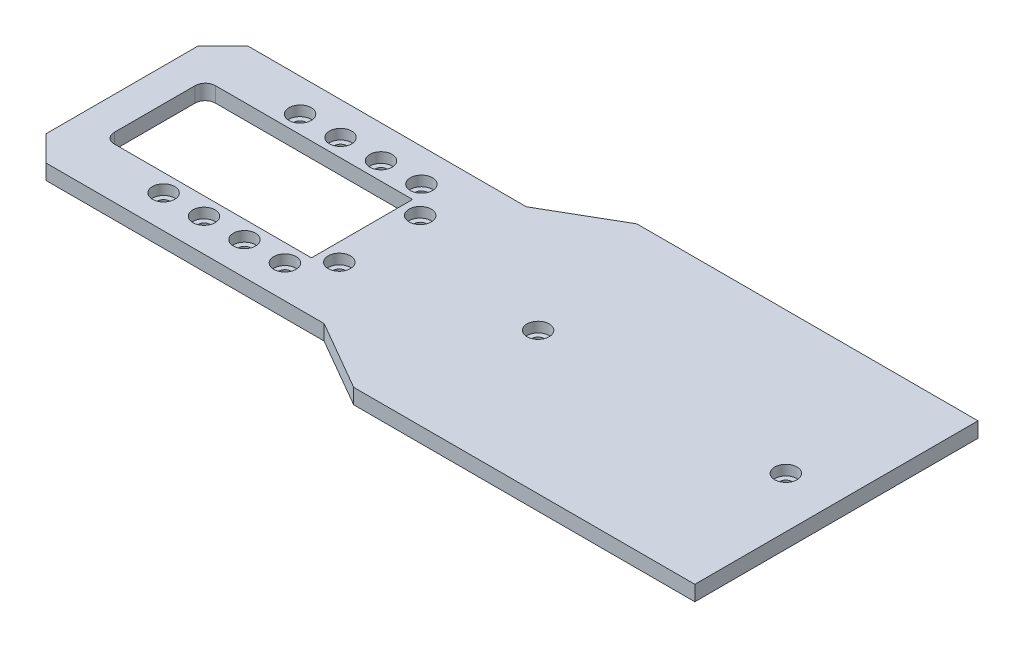
SolidWorks part; units mm, degrees
ref_plane "Front" through (0, 0, 0) normal (0, 0, 1) x (1, 0, 0)
ref_plane "Top" through (0, 0, 0) normal (0, 1, 0) x (1, 0, 0)
ref_plane "Right" through (0, 0, 0) normal (1, 0, 0) x (0, 0, -1)
sketch "草图1" plane through (0, 0, 0) normal (0, 1, 0) x (1, 0, 0)
  line L0 (-45.7157, 114) -> (45.7157, 114)
  line L1 (-74, 0) -> (74, 0) construction
  line L2 (74, -30) -> (91.3205, -20)
  line L3 (91.3205, -20) -> (146.3205, -20)
  line L4 (151.3205, -15) -> (151.3205, 15)
  line L5 (-60, 100) -> (60, -100) construction
  line L6 (-60, -100) -> (60, 100) construction
  line L7 (74, -30) -> (74, -85.7157)
  line L8 (-45.7157, -114) -> (45.7157, -114)
  line L9 (-74, 85.7157) -> (-74, 30)
  line L10 (146.3205, 20) -> (91.3205, 20)
  line L11 (74, 30) -> (91.3205, 20)
  line L12 (0, 100) -> (0, -100) construction
  line L13 (-74, 30) -> (-91.3205, 20)
  line L14 (-146.3205, 20) -> (-91.3205, 20)
  line L15 (-151.3205, -15) -> (-151.3205, 15)
  line L16 (-91.3205, -20) -> (-146.3205, -20)
  line L17 (-74, -30) -> (-91.3205, -20)
  line L18 (-74, -30) -> (-74, -85.7157)
  line L19 (74, 85.7157) -> (74, 30)
  line L20 (91.6777, 152.8909) -> (112.8909, 131.6777)
  line L21 (74, 85.7157) -> (112.8909, 124.6066)
  line L22 (45.7157, 114) -> (84.6066, 152.8909)
  line L23 (-74, 85.7157) -> (-112.8909, 124.6066)
  line L24 (-91.6777, 152.8909) -> (-112.8909, 131.6777)
  line L25 (-45.7157, 114) -> (-84.6066, 152.8909)
  line L26 (74, -85.7157) -> (112.8909, -124.6066)
  line L27 (91.6777, -152.8909) -> (112.8909, -131.6777)
  line L28 (45.7157, -114) -> (84.6066, -152.8909)
  line L29 (-74, -85.7157) -> (-112.8909, -124.6066)
  line L30 (-91.6777, -152.8909) -> (-112.8909, -131.6777)
  line L31 (-45.7157, -114) -> (-84.6066, -152.8909)
  line L32 (-84.6066, 152.8909) -> (-91.6777, 152.8909)
  line L33 (-112.8909, 131.6777) -> (-112.8909, 124.6066)
  line L34 (-151.3205, 15) -> (-146.3205, 20)
  line L35 (-146.3205, -20) -> (-151.3205, -15)
  line L36 (-112.8909, -124.6066) -> (-112.8909, -131.6777)
  line L37 (-84.6066, -152.8909) -> (-91.6777, -152.8909)
  line L38 (84.6066, -152.8909) -> (91.6777, -152.8909)
  line L39 (112.8909, -131.6777) -> (112.8909, -124.6066)
  line L40 (146.3205, -20) -> (151.3205, -15)
  line L41 (151.3205, 15) -> (146.3205, 20)
  line L42 (112.8909, 124.6066) -> (112.8909, 131.6777)
  line L43 (84.6066, 152.8909) -> (91.6777, 152.8909)
  point P0 (0, 0)
  point P12 (74, 30)
  point P16 (74, -30)
extrude "凸台-拉伸1" add sketch "草图1" along normal blind 3
sketch "草图2" plane through (0, 3, 0) normal (0, 1, 0) x (1, 0, 0)
  line L0 (151.3205, 0) -> (87.3942, 0) construction
  line L1 (151.3205, -15) -> (151.3205, 15) construction
  line L2 (103.8205, -10) -> (103.8205, 10)
  line L3 (103.8205, 10) -> (142.8205, 10)
  line L4 (103.8205, -10) -> (142.8205, -10)
  line L7 (144.8205, -15) -> (144.8205, 15)
  line L8 (144.8205, -8) -> (144.8205, 8)
  arc A0 (142.8205, -10) -> (144.8205, -8) centre (142.8205, -8) ccw
  arc A1 (144.8205, 8) -> (142.8205, 10) centre (142.8205, 8) ccw
  point P11 (103.8205, 0)
  dimension "D5" = 6.5
  dimension "D1" = 2
  dimension "D3" = 20
extrude "切除-拉伸1" cut sketch "草图2" against normal up to next
sketch "草图3" plane through (0, 3, 0) normal (0, 1, 0) x (1, 0, 0)
  line L0 (142.8205, 10) -> (103.8205, 10) construction
  line L1 (103.8205, 10) -> (103.8205, -10) construction
  line L2 (151.3205, 0) -> (86.0016, 0) construction
  line L3 (151.3205, -15) -> (151.3205, 15) construction
  point P0 (105.5705, 13.5)
  point P10 (100.3205, 8)
  point P12 (113.5705, 13.5)
  point P13 (121.5705, 13.5)
  point P14 (129.5705, 13.5)
  point P15 (129.5705, -13.5)
  point P16 (121.5705, -13.5)
  point P17 (113.5705, -13.5)
  point P18 (105.5705, -13.5)
  point P19 (100.3205, -8)
  dimension "D1" = 3.5
  dimension "D2" = 1.75
  dimension "D4" = 3.5
  dimension "D5" = 2
  dimension "D3" = 4
hole_wizard "M2 凹头盖螺钉的柱形沉头孔2" positions "3D草图1" profile "草图9" counterbore size "M2" standard "ANSI Metric" end condition through all
sketch3d "3D草图1"
  point P0 (100.3205, 3, -8)
  point P3 (105.5705, 3, -13.5)
  point P6 (113.5705, 3, -13.5)
  point P9 (121.5705, 3, -13.5)
  point P12 (129.5705, 3, -13.5)
  point P15 (100.3205, 3, 8)
  point P18 (105.5705, 3, 13.5)
  point P21 (113.5705, 3, 13.5)
  point P24 (121.5705, 3, 13.5)
  point P27 (129.5705, 3, 13.5)
sketch "草图9" plane through (100.3205, 3, -8) normal (1, 0, 0) x (0, 0, 1)
  line L0 (0, 0) -> (0, 3)
  line L1 (0, 3) -> (1.2, 3)
  line L3 (1.2, 3) -> (1.2, 2)
  line L4 (1.2, 2) -> (2.2, 2)
  line L5 (2.2, 2) -> (2.2, 0)
  line L7 (2.2, 0) -> (0, 0)
  line L11 (0, -6.35) -> (0, 107.95) construction
  dimension "通孔孔直径" = 2.4
  dimension "通孔孔深度" = 3
  dimension "柱形沉头孔直径" = 4.4
  dimension "柱形沉头孔深度" = 2
sketch "草图10" plane through (0, 3, 0) normal (0, 1, 0) x (1, 0, 0)
  line L0 (102.2843, 142.2843) -> (57.3662, 97.3662) construction
  line L1 (112.8909, 131.6777) -> (91.6777, 152.8909) construction
  line L2 (75.7678, 101.6256) -> (61.6256, 115.7678)
  line L3 (61.6256, 115.7678) -> (79.9162, 134.0583)
  line L4 (75.7678, 101.6256) -> (94.0583, 119.9162)
  line L5 (97.6881, 137.6881) -> (103.3449, 132.0312)
  line L6 (94.0583, 119.9162) -> (103.3449, 129.2028)
  line L7 (79.9162, 134.0583) -> (89.2028, 143.3449)
  line L8 (92.0312, 143.3449) -> (97.6881, 137.6881)
  arc A0 (103.3449, 129.2028) -> (103.3449, 132.0312) centre (101.9307, 130.617) ccw
  arc A1 (92.0312, 143.3449) -> (89.2028, 143.3449) centre (90.617, 141.9307) ccw
  point P9 (68.6967, 108.6967)
  dimension "D1" = 6.5
  dimension "D2" = 2
extrude "切除-拉伸2" cut sketch "草图10" against normal up to next
sketch "草图16" plane through (0, 3, 0) normal (0, 1, 0) x (1, 0, 0)
  line L0 (102.2843, 142.2843) -> (58.019, 98.019) construction
  line L1 (112.8909, 131.6777) -> (91.6777, 152.8909) construction
  line L2 (61.6256, 115.7678) -> (75.7678, 101.6256) construction
  line L3 (89.2028, 143.3449) -> (61.6256, 115.7678) construction
  line L4 (60.3882, 119.4801) -> (80.2149, 139.3067) construction
  point P0 (60.3882, 119.4801)
  point P1 (60.565, 111.8787)
  point P12 (66.045, 125.1369)
  point P13 (71.7019, 130.7938)
  point P14 (77.3588, 136.4506)
  point P15 (96.4506, 117.3588)
  point P16 (90.7938, 111.7019)
  point P17 (85.1369, 106.045)
  point P18 (79.4801, 100.3882)
  point P19 (71.8787, 100.565)
  dimension "D1" = 3.5
  dimension "D2" = 2
  dimension "D3" = 1.75
  dimension "D4" = 3.5
  dimension "D5" = 8
  dimension "D6" = 8
  dimension "D7" = 8
hole_wizard "M2 凹头盖螺钉的柱形沉头孔3" positions "3D草图3" profile "草图17" counterbore size "M2" standard "ANSI Metric" end condition through all
sketch3d "3D草图3"
  point P0 (60.3882, 3, -119.4801)
  point P3 (66.045, 3, -125.1369)
  point P6 (71.7019, 3, -130.7938)
  point P9 (77.3588, 3, -136.4506)
  point P12 (60.565, 3, -111.8787)
  point P15 (71.8787, 3, -100.565)
  point P18 (79.4801, 3, -100.3882)
  point P21 (85.1369, 3, -106.045)
  point P24 (90.7938, 3, -111.7019)
  point P27 (96.4506, 3, -117.3588)
sketch "草图17" plane through (60.3882, 3, -119.4801) normal (1, 0, 0) x (0, 0, 1)
  line L0 (0, 0) -> (0, 3)
  line L1 (0, 3) -> (1.2, 3)
  line L3 (1.2, 3) -> (1.2, 2)
  line L4 (1.2, 2) -> (2.2, 2)
  line L5 (2.2, 2) -> (2.2, 0)
  line L7 (2.2, 0) -> (0, 0)
  line L11 (0, -6.35) -> (0, 107.95) construction
  dimension "通孔孔直径" = 2.4
  dimension "通孔孔深度" = 3
  dimension "柱形沉头孔直径" = 4.4
  dimension "柱形沉头孔深度" = 2
mirror "镜向5" about plane through (0, 0, 0) normal (1, 0, 0) of "切除-拉伸1", "M2 凹头盖螺钉的柱形沉头孔2"
mirror "镜向6" about plane through (0, 0, 0) normal (1, 0, 0) of "切除-拉伸2", "M2 凹头盖螺钉的柱形沉头孔3"
mirror "镜向7" about plane through (0, 0, 0) normal (0, 0, 1) of "切除-拉伸2", "M2 凹头盖螺钉的柱形沉头孔3", "镜向6"
sketch "草图18" plane through (0, 3, 0) normal (0, 1, 0) x (1, 0, 0)
  line L0 (0, 114) -> (0, -114) construction
  line L1 (45.7157, 114) -> (-45.7157, 114) construction
  line L2 (-45.7157, -114) -> (45.7157, -114) construction
  line L3 (-151.3205, 0) -> (151.3205, 0) construction
  line L4 (-151.3205, 15) -> (-151.3205, -15) construction
  line L5 (-60, -28) -> (-15, -28)
  line L6 (-15, -28) -> (-15, -63)
  line L7 (-15, -63) -> (-60, -83)
  line L8 (-60, -83) -> (-60, -28)
  line L12 (10, -94) -> (30, -94)
  line L13 (-10, -94) -> (-30, -94)
  line L14 (-10, -94) -> (-10, -104)
  line L15 (-10, -104) -> (-30, -104)
  line L16 (-30, -94) -> (-30, -104)
  line L17 (-10, -94) -> (-30, -104) construction
  line L18 (-10, -104) -> (-30, -94) construction
  line L19 (10, -104) -> (30, -104)
  line L20 (10, -94) -> (10, -104)
  line L21 (30, -94) -> (30, -104)
  line L22 (15, -63) -> (60, -83)
  line L23 (60, -83) -> (60, -28)
  line L25 (15, -28) -> (15, -63)
  line L26 (60, -28) -> (15, -28)
  line L27 (-10, 104) -> (-30, 104)
  line L28 (-30, 94) -> (-30, 104)
  line L29 (-10, 94) -> (-30, 94)
  line L30 (-10, 94) -> (-10, 104)
  line L31 (30, 94) -> (30, 104)
  line L32 (10, 104) -> (30, 104)
  line L33 (10, 94) -> (10, 104)
  line L34 (10, 94) -> (30, 94)
  line L35 (15, 63) -> (60, 83)
  line L36 (60, 83) -> (60, 28)
  line L37 (60, 28) -> (15, 28)
  line L38 (15, 28) -> (15, 63)
  line L39 (-15, 28) -> (-15, 63)
  line L40 (-60, 28) -> (-15, 28)
  line L41 (-60, 83) -> (-60, 28)
  line L42 (-15, 63) -> (-60, 83)
  point P17 (-20, -99)
  point P32 (0, -20)
  point P33 (0, -10)
  dimension "D5" = 60
  dimension "D6" = 45
  dimension "D7" = 55
  dimension "D8" = 35
  dimension "D9" = 20
  dimension "D10" = 10
  dimension "D11" = 10
  dimension "D12" = 10
extrude "切除-拉伸3" cut sketch "草图18" against normal up to next
sketch "草图19" plane through (0, 3, 0) normal (0, 1, 0) x (1, 0, 0)
  line L0 (0, 114) -> (0, -114) construction
  line L1 (45.7157, 114) -> (-45.7157, 114) construction
  line L2 (-45.7157, -114) -> (45.7157, -114) construction
  line L3 (-151.3205, 0) -> (151.3205, 0) construction
  line L4 (-151.3205, 15) -> (-151.3205, -15) construction
  line L5 (-10, 94) -> (-10, 104) construction
  point P0 (-20, 109)
  point P14 (20, 109)
  point P15 (20, -109)
  point P16 (-20, -109)
  point P17 (-20, 0)
  point P18 (20, 0)
  dimension "D1" = 5
  dimension "D2" = 10
hole_wizard "M2 凹头盖螺钉的柱形沉头孔4" positions "3D草图4" profile "草图20" counterbore size "M2" standard "ANSI Metric" end condition through all
sketch3d "3D草图4"
  point P0 (-20, 3, 109)
  point P3 (20, 3, 109)
  point P6 (-20, 3, -109)
  point P9 (20, 3, -109)
sketch "草图20" plane through (-20, 3, 109) normal (1, 0, 0) x (0, 0, 1)
  line L0 (0, 0) -> (0, 3)
  line L1 (0, 3) -> (1.2, 3)
  line L3 (1.2, 3) -> (1.2, 2)
  line L4 (1.2, 2) -> (2.2, 2)
  line L5 (2.2, 2) -> (2.2, 0)
  line L7 (2.2, 0) -> (0, 0)
  line L11 (0, -6.35) -> (0, 107.95) construction
  dimension "通孔孔直径" = 2.4
  dimension "通孔孔深度" = 3
  dimension "柱形沉头孔直径" = 4.4
  dimension "柱形沉头孔深度" = 2
sketch "草图21" plane through (0, 3, 0) normal (0, 1, 0) x (1, 0, 0)
  line L0 (-74, 85.7157) -> (-74, 30) construction
  line L1 (74, 30) -> (74, 85.7157) construction
  line L2 (-60, 28) -> (-15, 28) construction
  line L3 (15, 28) -> (60, 28) construction
  point P0 (-69, 40)
  point P1 (69, 40)
  point P6 (-69, 0)
  point P11 (69, 0)
  dimension "D1" = 5
  dimension "D2" = 5
  dimension "D3" = 12
  dimension "D4" = 12
  dimension "D5" = 40
hole_wizard "M2 凹头盖螺钉的柱形沉头孔5" positions "3D草图5" profile "草图22" counterbore size "M2" standard "ANSI Metric" end condition through all
sketch3d "3D草图5"
  point P0 (-69, 3, -40)
  point P3 (69, 3, -40)
sketch "草图22" plane through (-69, 3, -40) normal (1, 0, 0) x (0, 0, 1)
  line L0 (0, 0) -> (0, 3)
  line L1 (0, 3) -> (1.2, 3)
  line L3 (1.2, 3) -> (1.2, 2)
  line L4 (1.2, 2) -> (2.2, 2)
  line L5 (2.2, 2) -> (2.2, 0)
  line L7 (2.2, 0) -> (0, 0)
  line L11 (0, -6.35) -> (0, 107.95) construction
  dimension "通孔孔直径" = 2.4
  dimension "通孔孔深度" = 3
  dimension "柱形沉头孔直径" = 4.4
  dimension "柱形沉头孔深度" = 2
mirror "镜向8" about plane through (0, 0, 0) normal (0, 0, 1) of "M2 凹头盖螺钉的柱形沉头孔5"
hole_wizard "M2 凹头盖螺钉的柱形沉头孔6" positions "3D草图6" profile "草图23" counterbore size "M2" standard "ANSI Metric" end condition through all
sketch3d "3D草图6"
  point P0 (-69, 3, 0)
  point P3 (69, 3, 0)
sketch "草图23" plane through (-69, 3, 0) normal (1, 0, 0) x (0, 0, 1)
  line L0 (0, 0) -> (0, 3)
  line L1 (0, 3) -> (1.2, 3)
  line L3 (1.2, 3) -> (1.2, 2)
  line L4 (1.2, 2) -> (2.2, 2)
  line L5 (2.2, 2) -> (2.2, 0)
  line L7 (2.2, 0) -> (0, 0)
  line L11 (0, -6.35) -> (0, 107.95) construction
  dimension "通孔孔直径" = 2.4
  dimension "通孔孔深度" = 3
  dimension "柱形沉头孔直径" = 4.4
  dimension "柱形沉头孔深度" = 2
sketch "草图24" plane through (0, 3, 0) normal (0, 1, 0) x (1, 0, 0)
  line L3 (-10, 28) -> (10, 28)
  line L4 (-10, 28) -> (-10, -28)
  line L5 (-10, -28) -> (10, -28)
  line L6 (10, 28) -> (10, -28)
  line L7 (-10, 28) -> (10, -28) construction
  line L8 (-10, -28) -> (10, 28) construction
  point P0 (0, 0)
  dimension "D1" = 20
  dimension "D2" = 56
extrude "切除-拉伸4" cut sketch "草图24" against normal blind 10
hole_wizard "M2 凹头盖螺钉的柱形沉头孔7" positions "3D草图7" profile "草图25" counterbore size "M2" standard "ANSI Metric" end condition through all
sketch3d "3D草图7"
  point P0 (-20, 3, 0)
  point P3 (20, 3, 0)
sketch "草图25" plane through (-20, 3, 0) normal (1, 0, 0) x (0, 0, 1)
  line L0 (0, 0) -> (0, 3)
  line L1 (0, 3) -> (1.2, 3)
  line L3 (1.2, 3) -> (1.2, 2)
  line L4 (1.2, 2) -> (2.2, 2)
  line L5 (2.2, 2) -> (2.2, 0)
  line L7 (2.2, 0) -> (0, 0)
  line L11 (0, -6.35) -> (0, 107.95) construction
  dimension "通孔孔直径" = 2.4
  dimension "通孔孔深度" = 3
  dimension "柱形沉头孔直径" = 4.4
  dimension "柱形沉头孔深度" = 2
sketch "草图26" plane through (0, 3, 0) normal (0, 1, 0) x (1, 0, 0)
  line L1 (-151.3205, 28) -> (-10, 28)
  line L2 (-151.3205, 28) -> (-151.3205, -28)
  line L3 (-151.3205, -28) -> (-10, -28)
  line L4 (-10, 28) -> (-10, -28)
extrude "切除-拉伸5" cut sketch "草图26" against normal blind 10 flip side to cut
